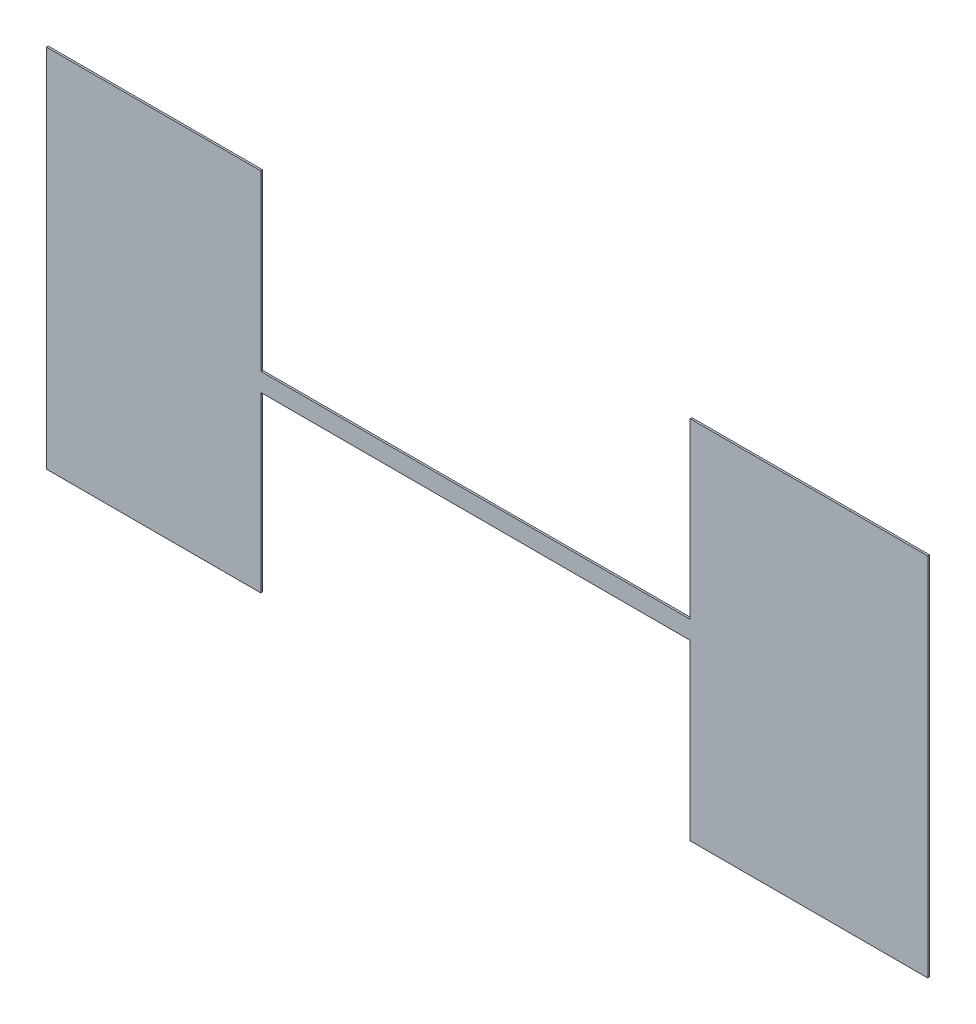
SolidWorks part; units mm, degrees
ref_plane "Front Plane" through (0, 0, 0) normal (0, 0, 1) x (1, 0, 0)
ref_plane "Top Plane" through (0, 0, 0) normal (0, 1, 0) x (1, 0, 0)
ref_plane "Right Plane" through (0, 0, 0) normal (1, 0, 0) x (0, 0, -1)
sketch "Sketch1" plane through (0, 0, 0) normal (0, 0, 1) x (1, 0, 0)
  line L0 (-650, 0) -> (523, 0) construction
  line L1 (-650, 1000) -> (523, 1000)
  line L2 (-650, 1000) -> (-650, -1000)
  line L3 (-650, -1000) -> (523, -1000)
  line L4 (523, 1000) -> (523, 50)
  line L5 (-650, 0) -> (0, 0) construction
  line L6 (0, 0) -> (2359.0404, 0) construction
  line L7 (523, -50) -> (523, -1000)
  line L8 (2872.5, -50) -> (523, -50)
  line L10 (2872.5, 50) -> (523, 50)
  line L12 (2872.5, -50) -> (523, 50) construction
  line L13 (2872.5, 50) -> (523, -50) construction
  line L14 (2872.5, -1000) -> (2872.5, -50) construction
  line L15 (2872.5, 50) -> (2872.5, 576.5166) construction
  line L16 (4172.5, -1000) -> (2872.5, -1000)
  line L17 (4172.5, -1000) -> (4172.5, 1000)
  line L18 (4172.5, 1000) -> (2872.5, 1000)
  line L19 (2872.5, -1000) -> (2872.5, -50)
  line L20 (4172.5, -1000) -> (2872.5, 1000) construction
  line L21 (4172.5, 1000) -> (2872.5, -1000) construction
  line L22 (2872.5, 50) -> (2872.5, 1000)
  point P4 (-650, 0)
  point P5 (523, 0)
  point P8 (-63.5, 0)
  point P11 (1697.75, 0)
  point P12 (3522.5, 0)
  dimension "D1" = 1173
  dimension "D2" = 650
  dimension "D3" = 2000
  dimension "D4" = 2349.5
  dimension "D5" = 100
  dimension "D6" = 1300
  dimension "D7" = 2000
extrude "Boss-Extrude1" add sketch "Sketch1" along normal blind 10
